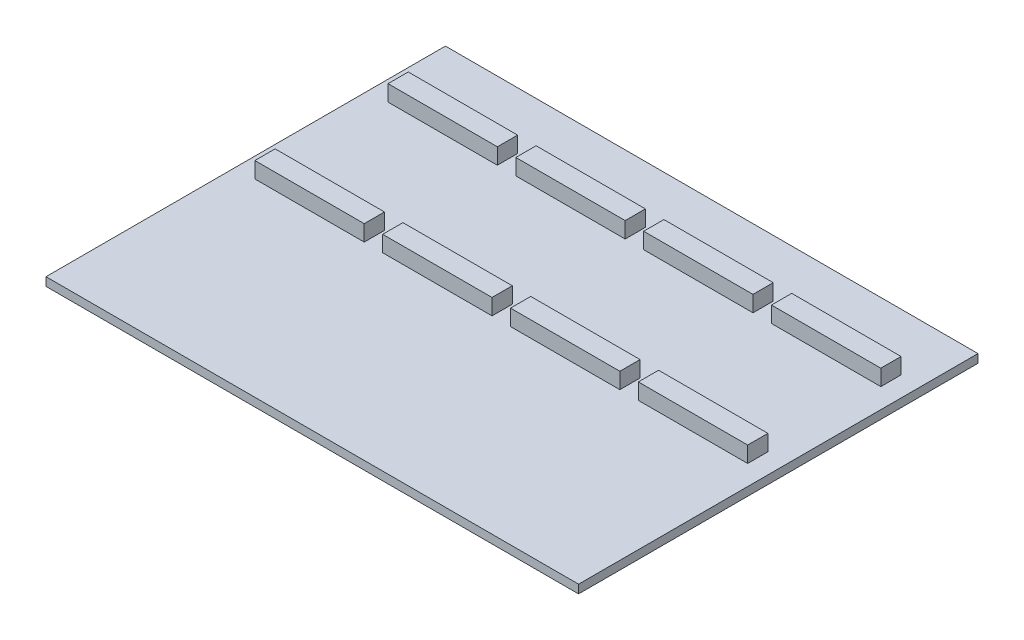
SolidWorks part; units mm, degrees
ref_plane "Front Plane" through (0, 0, 0) normal (0, 0, 1) x (1, 0, 0)
ref_plane "Top Plane" through (0, 0, 0) normal (0, 1, 0) x (1, 0, 0)
ref_plane "Right Plane" through (0, 0, 0) normal (1, 0, 0) x (0, 0, -1)
sketch "Sketch1" plane through (0, 0, 0) normal (0, 1, 0) x (1, 0, 0)
  line L1 (0, 0) -> (100, 0)
  line L2 (0, 0) -> (0, 75)
  line L3 (0, 75) -> (100, 75)
  line L4 (100, 0) -> (100, 75)
extrude "Boss-Extrude1" add sketch "Sketch1" along normal blind 1.5875
sketch "Sketch2" plane through (0, 0, 0) normal (0, 1, 0) x (1, 0, 0)
  line L1 (3.72, 39.3) -> (24.25, 39.3)
  line L2 (3.72, 39.3) -> (3.72, 35.5)
  line L3 (3.72, 35.5) -> (24.25, 35.5)
  line L4 (24.25, 39.3) -> (24.25, 35.5)
extrude "Boss-Extrude2" add sketch "Sketch2" along normal blind 4.5875
pattern_linear "LPattern1" count 4 spacing 24 along (1, 0, 0) count 2 spacing 25 along (0, 0, -1) of "Boss-Extrude2"
sketch "Sketch3" plane through (0, 0, -75) normal (0, 0, -1) x (-1, 0, 0)
  line L1 (-5.75, -1.375) -> (-22, -1.375)
  line L2 (-5.75, -1.375) -> (-5.75, 2.875)
  line L3 (-5.75, 2.875) -> (-22, 2.875)
  line L4 (-22, -1.375) -> (-22, 2.875)
